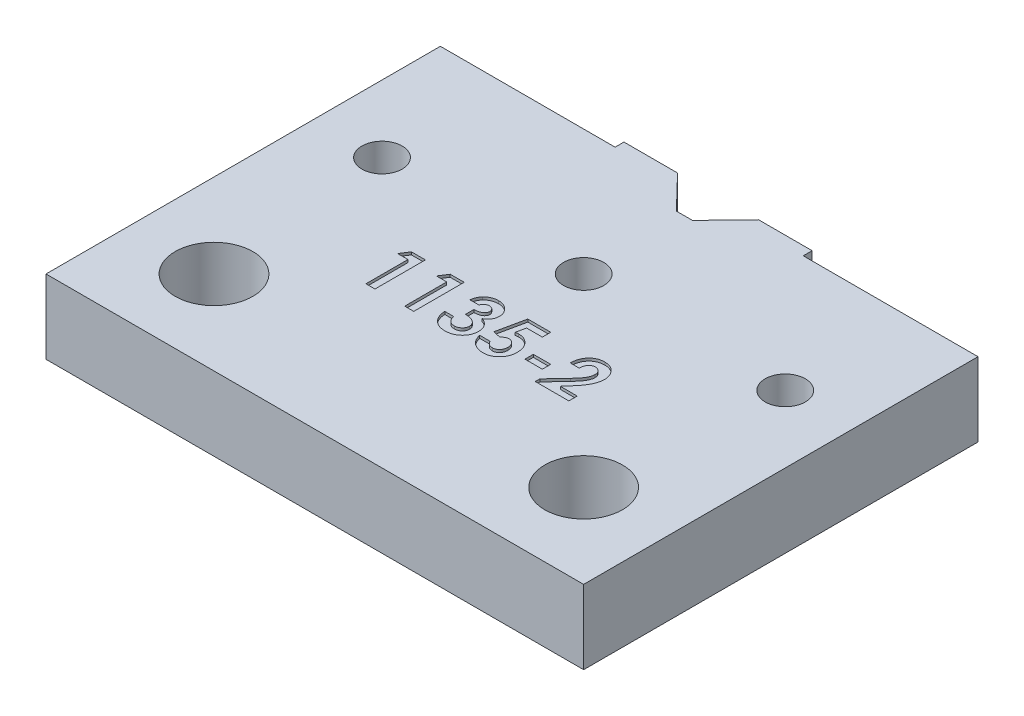
SolidWorks part; units mm, degrees
material "S7"
ref_plane "Alzado" through (0, 0, 0) normal (0, 0, 1) x (1, 0, 0)
ref_plane "Planta" through (0, 0, 0) normal (0, 1, 0) x (1, 0, 0)
ref_plane "Vista lateral" through (0, 0, 0) normal (1, 0, 0) x (0, 0, -1)
sketch "Croquis1" plane through (0, 0, 0) normal (0, 1, 0) x (1, 0, 0)
  line L1 (50.8, -38.1) -> (0, -38.1)
  line L2 (50.8, -38.1) -> (50.8, 0)
  line L3 (50.8, 0) -> (0, 0)
  line L4 (0, -38.1) -> (0, 0)
  line L5 (25.4, 0) -> (25.4, -38.1) construction
  line L6 (50.8, -19.05) -> (0, -19.05) construction
  point P220 (25.4, -19.05)
  dimension "D1" = 50.8
  dimension "D2" = 38.1
extrude "Saliente-Extruir1" add sketch "Croquis1" along normal blind 6.985
sketch "Croquis2" plane through (0, 6.985, 0) normal (0, 1, 0) x (1, 0, 0)
  line L0 (21.5719, 0) -> (24.638, -3.175)
  line L1 (50.8, 0) -> (0, 0) construction
  line L2 (24.638, -3.175) -> (26.162, -3.175)
  line L3 (26.162, -3.175) -> (29.2281, 0)
  line L4 (29.2281, 0) -> (21.5719, 0)
  line L5 (25.4, -3.175) -> (25.4, 0) construction
  line L6 (0, -0.8382) -> (0, 0)
  line L7 (0, 0) -> (0, -38.1) construction
  line L8 (0, 0) -> (16.51, 0)
  line L9 (16.51, 0) -> (16.51, -0.8382)
  line L10 (16.51, -0.8382) -> (0, -0.8382)
  line L11 (34.29, -0.8382) -> (50.8, -0.8382)
  line L12 (34.29, 0) -> (34.29, -0.8382)
  line L13 (50.8, 0) -> (34.29, 0)
  line L14 (50.8, -0.8382) -> (50.8, 0)
  dimension "D1" = 1.524
  dimension "D2" = 88
  dimension "D3" = 3.175
  dimension "D4" = 2.3368
  dimension "D5" = 16.51
extrude "Cortar-Extruir1" cut sketch "Croquis2" against normal through all
hole_wizard "Taladro roscado #10-241" positions "Croquis3" profile "Croquis4" tap size "#10-24" standard "Ansi Inch" end condition through all
sketch "Croquis3" plane through (0, 6.985, 0) normal (0, 1, 0) x (1, 0, 0)
  line L0 (6.35, -12.7) -> (44.45, -12.7) construction
  line L2 (0, -0.8382) -> (0, -38.1) construction
  line L3 (6.35, -12.7) -> (6.35, -38.1) construction
  line L4 (0, -38.1) -> (50.8, -38.1) construction
  point P0 (6.35, -12.7)
  point P2 (44.45, -12.7)
  point P19 (25.4, -12.7)
  dimension "D1" = 6.35
  dimension "D2" = 44.45
  dimension "D3" = 25.4
sketch "Croquis4" plane through (6.35, 6.985, 12.7) normal (1, 0, 0) x (0, 0, 1)
  line L0 (0, 0) -> (0, 6.985)
  line L1 (0, 6.985) -> (1.8986, 6.985)
  line L2 (1.8986, 6.985) -> (1.8986, 0)
  line L5 (1.8986, 0) -> (0, 0)
  line L11 (0, -6.35) -> (0, 107.95) construction
  dimension "Diámetro de perforador para roscar hasta el siguiente" = 3.7973
  dimension "Profundidad de perforador para roscar hasta el siguiente" = 6.985
cosmetic thread "Rosca de taladro1" parameters "D2"=4.826
cosmetic thread "Rosca de taladro2" parameters "D2"=4.826
cosmetic thread "Rosca de taladro3" parameters "D2"=4.826
sketch "Croquis5" plane through (0, 6.985, 0) normal (0, 1, 0) x (1, 0, 0)
  line L0 (7.9375, -30.1625) -> (42.8625, -30.1625) construction
  line L1 (25.4, -38.1) -> (25.4, -30.1625) construction
  line L2 (0, -38.1) -> (50.8, -38.1) construction
  line L3 (0, -0.8382) -> (0, -38.1) construction
  circle A0 centre (7.9375, -30.1625) radius 3.6703
  circle A1 centre (42.8625, -30.1625) radius 3.6703
  dimension "D3" = 7.3406
  dimension "D1" = 7.9375
  dimension "D2" = 7.9375
extrude "Cortar-Extruir2" cut sketch "Croquis5" against normal through all
sketch "Croquis6" plane through (0, 6.985, 0) normal (0, 1, 0) x (1, 0, 0)
  line L0 (42.6693, -23.7873) -> (7.1789, -23.7873) construction
  text T0 "1135-2" font "Century Gothic" height 4.7625
extrude "Cortar-Extruir3" cut sketch "Croquis6" against normal blind 0.254
